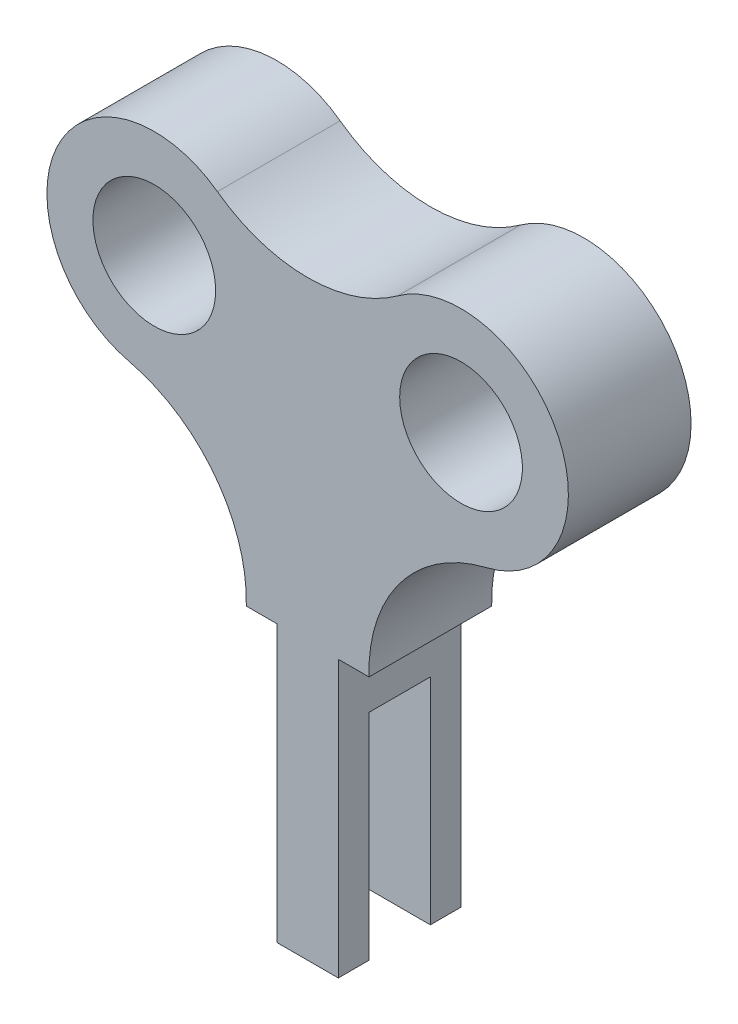
SolidWorks part; units mm, degrees
ref_plane "Ön Düzlem" through (0, 0, 0) normal (0, 0, 1) x (1, 0, 0)
ref_plane "Üst Düzlem" through (0, 0, 0) normal (0, 1, 0) x (1, 0, 0)
ref_plane "Sağ Düzlem" through (0, 0, 0) normal (1, 0, 0) x (0, 0, -1)
sketch "Çizim1" plane through (0, 0, 0) normal (0, 0, 1) x (1, 0, 0)
  line L0 (0, 78.8849) -> (0, -71.1151) construction
  line L1 (-77.5504, 33.8849) -> (122.4496, 33.8849) construction
  line L2 (-10, -8.1151) -> (-5, -8.1151)
  line L4 (-5, -8.1151) -> (-5, -53.1151)
  line L5 (-5, -53.1151) -> (5, -53.1151)
  line L6 (5, -8.1151) -> (5, -53.1151)
  line L7 (5, -8.1151) -> (10, -8.1151)
  circle A0 centre (-25, 33.8849) radius 10
  circle A1 centre (25, 33.8849) radius 10
  arc A2 (-14.7059, 48.037) -> (14.7059, 48.037) centre (0, 68.2543) ccw
  arc A3 (-10, -8.1151) -> (-29.1137, 16.8753) centre (-34.9905, -7.4242) ccw
  arc A4 (-14.7059, 48.037) -> (-29.1137, 16.8753) centre (-25, 33.8849) ccw
  arc A5 (14.7059, 48.037) -> (29.1137, 16.8753) centre (25, 33.8849) cw
  arc A6 (10, -8.1151) -> (29.1137, 16.8753) centre (34.9905, -7.4242) cw
  point P10 (-25, 4.1518)
  point P12 (-90.4611, -42.4143)
  point P22 (-34.6382, -8.1151)
  point P24 (-45.0771, -8.1151)
  point P27 (0, 0)
  dimension "D1" = 20
  dimension "D3" = 50
  dimension "D8" = 50
  dimension "D11" = 35
  dimension "D2" = 50
  dimension "D4" = 10
  dimension "D6" = 20
  dimension "D7" = 5
  dimension "D9" = 45
  dimension "D10" = 87
extrude "Yükseklik-Ekstrüzyon1" add sketch "Çizim1" along normal blind 20
sketch "Çizim3" plane through (5, 0, 0) normal (1, 0, 0) x (0, 0, -1)
  line L0 (-20, -53.1151) -> (0, -53.1151) construction
  line L1 (-15, -53.1151) -> (-5, -53.1151)
  line L2 (-15, -53.1151) -> (-15, -18.1151)
  line L3 (-15, -18.1151) -> (-5, -18.1151)
  line L4 (-5, -53.1151) -> (-5, -18.1151)
  line L5 (0, -53.1151) -> (0, -8.1151) construction
  dimension "D1" = 35
  dimension "D2" = 5
  dimension "D3" = 10
extrude "Kes-Ekstrüzyon1" cut sketch "Çizim3" against normal blind 10
